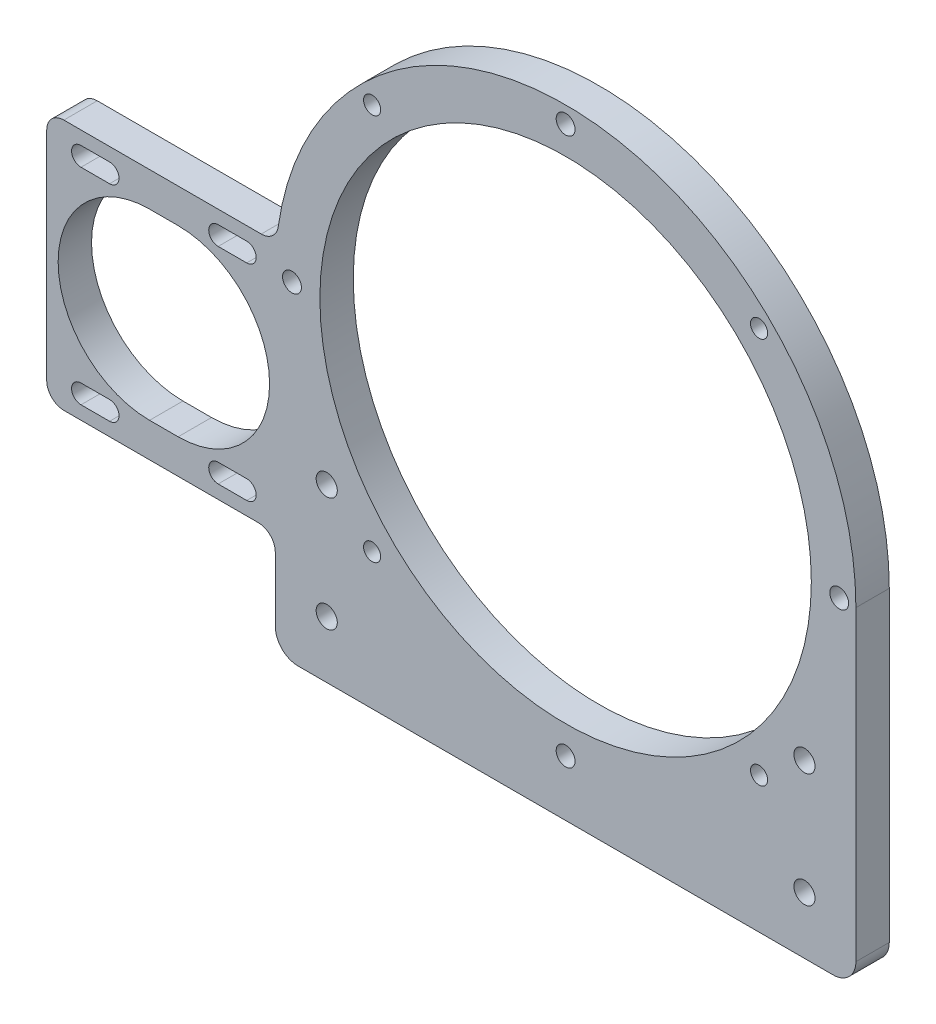
SolidWorks part; units mm, degrees
material "Acrylic (Medium-high impact)"
ref_plane "Front Plane" through (0, 0, 0) normal (0, 0, 1) x (1, 0, 0)
ref_plane "Top Plane" through (0, 0, 0) normal (0, 1, 0) x (1, 0, 0)
ref_plane "Right Plane" through (0, 0, 0) normal (1, 0, 0) x (0, 0, -1)
sketch "Sketch1" plane through (0, 0, 0) normal (0, 0, 1) x (1, 0, 0)
  line L0 (-50.8, 0) -> (-50.8, -57.658)
  line L1 (-50.8, 0) -> (-44.958, 0) construction
  line L2 (0, 0) -> (0, -57.658) construction
  line L3 (0, 0) -> (0, -62.9374) construction
  line L4 (50.8, 0) -> (50.8, -57.658)
  line L5 (-33.8556, 33.8556) -> (0, 0) construction
  line L8 (0, 0) -> (0, 47.879) construction
  line L12 (-50.8, -57.658) -> (0, -57.658)
  line L13 (-41.8, -57.658) -> (-41.8, -47.658) construction
  line L14 (-41.8, -47.658) -> (-41.8, -27.658) construction
  line L19 (0, -57.658) -> (50.8, -57.658)
  circle A1 centre (0, 0) radius 43
  arc A2 (-50.8, 0) -> (50.8, 0) centre (0, 0) cw
  circle A3 centre (-47.879, 0) radius 1.65
  circle A4 centre (0, 47.879) radius 1.65
  circle A6 centre (47.879, 0) radius 1.65
  circle A7 centre (0, -47.879) radius 1.65
  circle A10 centre (-41.8, -27.658) radius 1.85
  circle A11 centre (-33.8556, 33.8556) radius 1.5
  circle A12 centre (33.8556, 33.8556) radius 1.5
  circle A13 centre (33.8556, -33.8556) radius 1.5
  circle A14 centre (-33.8556, -33.8556) radius 1.5
  circle A15 centre (-41.8, -47.658) radius 1.85
  circle A16 centre (41.8, -47.658) radius 1.85
  circle A17 centre (41.8, -27.658) radius 1.85
  point P29 (0, 0)
  point P46 (0, 0)
  dimension "D2" = 86
  dimension "D5" = 3.3
  dimension "D6" = 4
  dimension "D7" = 45
  dimension "D10" = 62.9374
  dimension "D14" = 3
  dimension "D17" = 3.7
  dimension "D3" = 57.658
  dimension "D4" = 101.6
  dimension "D13" = 2.921
  dimension "D18" = 20
  dimension "D19" = 10
  dimension "D20" = 9
  dimension "D15" = 4
extrude "Boss-Extrude1" add sketch "Sketch1" along normal blind 5.842
fillet "Fillet1" radius 4 2 edges at (50.8, -57.658, 2.921) (-50.8, -57.658, 2.921)
sketch "Sketch2" plane through (0, 0, 5.842) normal (0, 0, 1) x (1, 0, 0)
  line L0 (-50.5923, 4.5885) -> (-90.8, 4.5885)
  line L1 (-67.8, -17.4115) -> (-67.8, -39.4115) construction
  line L2 (-90.8, 4.5885) -> (-90.8, -39.4115)
  line L3 (-90.8, -39.4115) -> (-50.8, -39.4115)
  line L4 (-67.8, -17.4115) -> (-90.8, -17.4115) construction
  line L5 (-50.5923, 4.5885) -> (-50.8, -39.4115)
  line L6 (-79.8, 0.5885) -> (-79.8, -35.4115) construction
  line L7 (-67.8, -17.4115) -> (-72.8, -17.4115) construction
  line L8 (-55.8, -35.4115) -> (-55.8, 0.5885) construction
  line L9 (-55.8, 0.5885) -> (-79.8, 0.5885) construction
  line L10 (-79.8, 0.5885) -> (-67.8, -17.4115) construction
  line L11 (-67.8, -17.4115) -> (-79.8, -35.4115) construction
  line L12 (-55.8, -35.4115) -> (-67.8, -17.4115) construction
  line L13 (-67.8, -17.4115) -> (-55.8, 0.5885) construction
  line L14 (-67.8, -17.4115) -> (0, 0) construction
  line L15 (-79.8, 0.5885) -> (-84.8, 0.5885) construction
  line L16 (-67.8, -33.4115) -> (-72.8, -33.4115)
  line L17 (-67.8, -1.4115) -> (-72.8, -1.4115)
  line L18 (-50.8, 0) -> (-50.8, -53.658) construction
  line L19 (-79.8, -1.0615) -> (-84.8, -1.0615)
  line L20 (-79.8, 2.2385) -> (-84.8, 2.2385)
  line L21 (-55.8, 0.5885) -> (-60.8, 0.5885) construction
  line L22 (-55.8, -1.0615) -> (-60.8, -1.0615)
  line L23 (-55.8, 2.2385) -> (-60.8, 2.2385)
  line L24 (-55.8, -35.4115) -> (-60.8, -35.4115) construction
  line L26 (-55.8, -37.0615) -> (-60.8, -37.0615)
  line L27 (-55.8, -33.7615) -> (-60.8, -33.7615)
  line L28 (-79.8, -35.4115) -> (-84.8, -35.4115) construction
  line L29 (-79.8, -37.0615) -> (-84.8, -37.0615)
  line L30 (-79.8, -33.7615) -> (-84.8, -33.7615)
  arc A0 (-67.8, -33.4115) -> (-67.8, -1.4115) centre (-67.8, -17.4115) ccw
  arc A1 (-79.8, -1.0615) -> (-79.8, 2.2385) centre (-79.8, 0.5885) ccw
  arc A2 (-84.8, 2.2385) -> (-84.8, -1.0615) centre (-84.8, 0.5885) ccw
  arc A3 (-55.8, -1.0615) -> (-55.8, 2.2385) centre (-55.8, 0.5885) ccw
  arc A4 (-60.8, 2.2385) -> (-60.8, -1.0615) centre (-60.8, 0.5885) ccw
  arc A5 (-72.8, -1.4115) -> (-72.8, -33.4115) centre (-72.8, -17.4115) ccw
  arc A6 (50.8, 0) -> (-50.8, 0) centre (0, 0) ccw construction
  arc A7 (-55.8, -37.0615) -> (-55.8, -33.7615) centre (-55.8, -35.4115) ccw
  arc A8 (-60.8, -33.7615) -> (-60.8, -37.0615) centre (-60.8, -35.4115) ccw
  arc A9 (-79.8, -37.0615) -> (-79.8, -33.7615) centre (-79.8, -35.4115) ccw
  arc A10 (-84.8, -33.7615) -> (-84.8, -37.0615) centre (-84.8, -35.4115) ccw
  point P1 (-70.3, -17.4115)
  point P7 (-82.3, 0.5885)
  point P27 (-58.3, 0.5885)
  point P34 (-58.3, -35.4115)
  point P41 (-82.3, -35.4115)
  dimension "D2" = 5
  dimension "D6" = 1.65
  dimension "D7" = 16
  dimension "D3" = 70
  dimension "D4" = 11
  dimension "D5" = 4
  dimension "D8" = 24
  dimension "D9" = 4
  dimension "D10" = 18
  dimension "D11" = 5
  dimension "D12" = 17
extrude "Boss-Extrude2" add sketch "Sketch2" against normal through all
fillet "Fillet2" radius 3 4 edges at (-50.8, -39.4115, 2.921) (-90.8, -39.4115, 2.921) (-90.8, 4.5885, 2.921) (-50.5923, 4.5885, 2.921)
